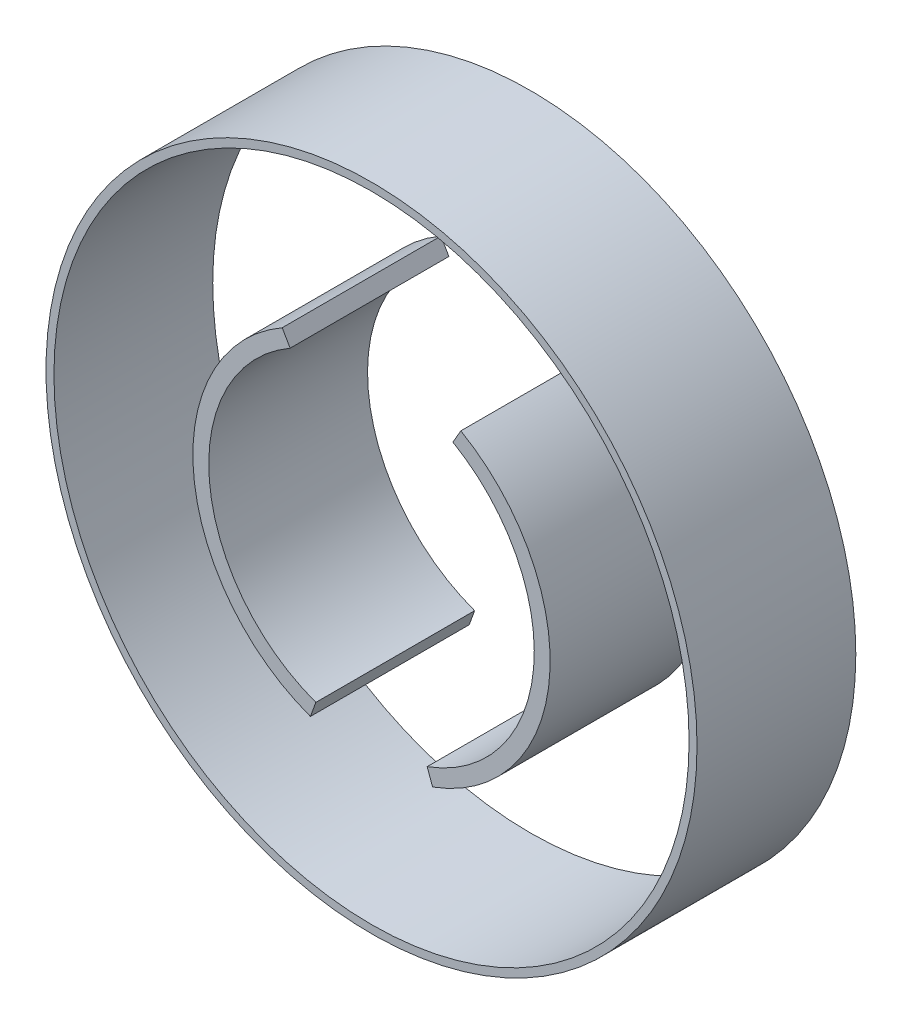
SolidWorks part; units mm, degrees
material "石膏板墙"
ref_plane "前视基准面" through (0, 0, 0) normal (0, 0, 1) x (1, 0, 0)
ref_plane "上视基准面" through (0, 0, 0) normal (0, 1, 0) x (1, 0, 0)
ref_plane "右视基准面" through (0, 0, 0) normal (1, 0, 0) x (0, 0, -1)
sketch "草图1" plane through (0, 0, 0) normal (0, 0, 1) x (1, 0, 0)
  circle A0 centre (0, 0) radius 4000
  circle A1 centre (0, 0) radius 4100
  dimension "D1" = 8000
  dimension "D2" = 8200
extrude "凸台-拉伸1" add sketch "草图1" along normal blind 2000
sketch "草图2" plane through (0, 0, 0) normal (0, 0, 1) x (1, 0, 0)
  line L0 (0, 0) -> (-769.5453, -2114.3084) construction
  line L1 (0, 0) -> (769.5453, -2114.3084) construction
  line L2 (0, 0) -> (0, -2250) construction
  line L3 (0, 0) -> (-1125, 1948.5572) construction
  line L4 (0, 0) -> (1125, 1948.5572) construction
  line L5 (-769.5453, -2114.3084) -> (-701.1413, -1926.3699)
  line L6 (769.5453, -2114.3084) -> (701.1413, -1926.3699)
  line L7 (-1125, 1948.5572) -> (-1025, 1775.3521)
  line L8 (1125, 1948.5572) -> (1025, 1775.3521)
  arc A0 (701.1413, -1926.3699) -> (1025, 1775.3521) centre (0, 0) ccw
  arc A1 (769.5453, -2114.3084) -> (1125, 1948.5572) centre (0, 0) ccw
  arc A2 (-1025, 1775.3521) -> (-701.1413, -1926.3699) centre (0, 0) ccw
  arc A3 (-1125, 1948.5572) -> (-769.5453, -2114.3084) centre (0, 0) ccw
  dimension "D1" = 4100
  dimension "D2" = 4500
  dimension "D3" = 40
  dimension "D4" = 60
extrude "凸台-拉伸2" add sketch "草图2" along normal blind 2000 separate body
